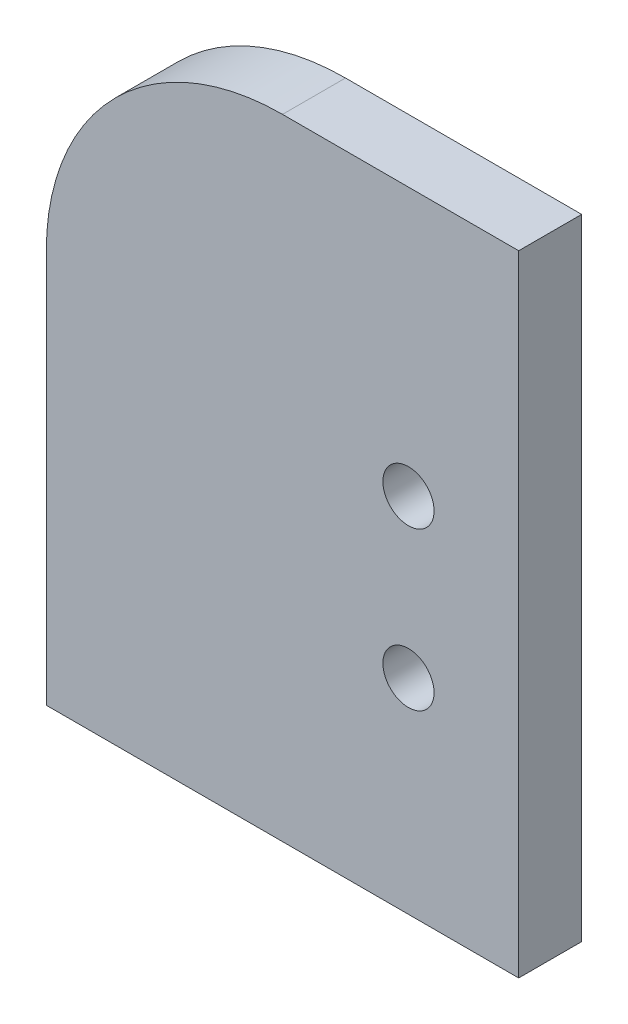
SolidWorks part; units mm, degrees
ref_plane "Ebene vorne" through (0, 0, 0) normal (0, 0, 1) x (1, 0, 0)
ref_plane "Ebene oben" through (0, 0, 0) normal (0, 1, 0) x (1, 0, 0)
ref_plane "Ebene rechts" through (0, 0, 0) normal (1, 0, 0) x (0, 0, -1)
sketch "Sketch1" plane through (0, 0, 0) normal (0, 0, 1) x (1, 0, 0)
  line L0 (0, 35) -> (0, 40)
  line L1 (0, 0) -> (-30, 0)
  line L2 (0, 0) -> (0, 35)
  line L3 (-15, 40) -> (0, 40)
  line L4 (-30, 0) -> (-30, 25)
  arc A0 (-15, 40) -> (-30, 25) centre (-15, 25) ccw
  dimension "D1" = 35
  dimension "D2" = 30
extrude "Boss-Extrude1" add sketch "Sketch1" along normal blind 4
sketch "Sketch2" plane through (0, 0, 4) normal (0, 0, 1) x (1, 0, 0)
  line L0 (0, 0) -> (0, 40) construction
  line L1 (-30, 0) -> (0, 0) construction
  circle A0 centre (-7, 23) radius 1.625
  circle A1 centre (-7, 13) radius 1.625
  dimension "D1" = 3.25
  dimension "D2" = 7
  dimension "D3" = 10
  dimension "D4" = 13
extrude "Cut-Extrude1" cut sketch "Sketch2" against normal through all
